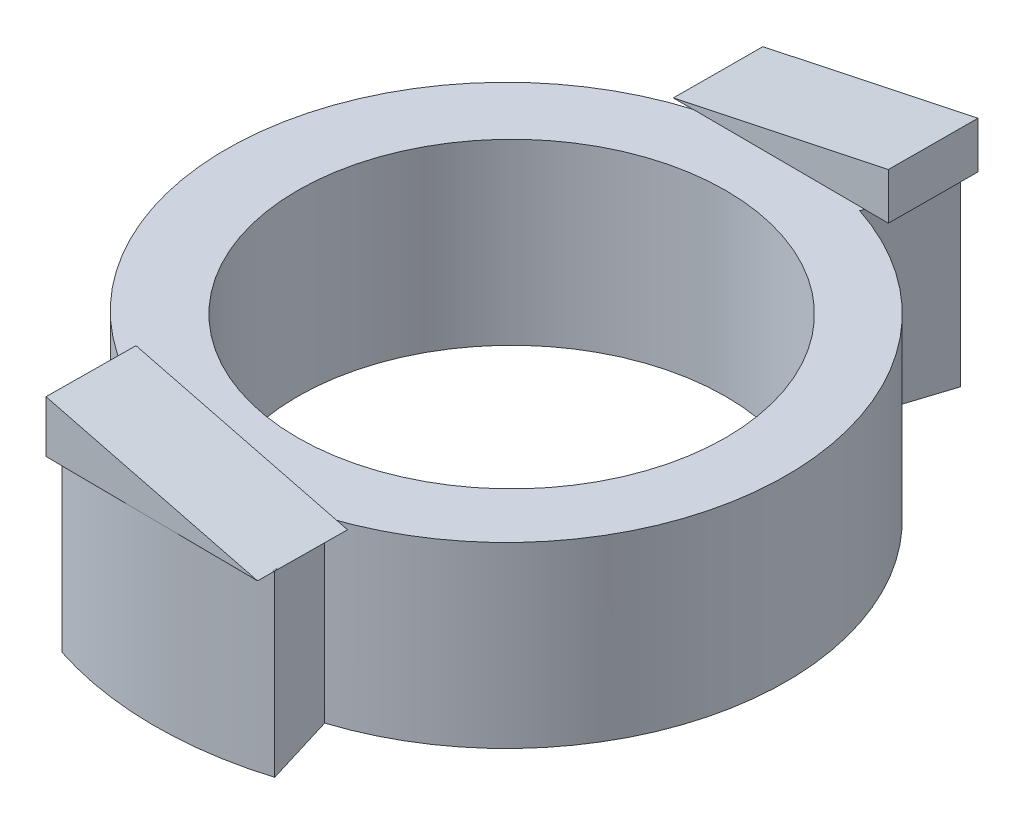
SolidWorks part; units mm, degrees
ref_plane "Front" through (0, 0, 0) normal (0, 0, 1) x (1, 0, 0)
ref_plane "Top" through (0, 0, 0) normal (0, 1, 0) x (1, 0, 0)
ref_plane "Right" through (0, 0, 0) normal (1, 0, 0) x (0, 0, -1)
sketch "Sketch1" plane through (0, 0, 0) normal (0, 1, 0) x (1, 0, 0)
  line L1 (0, -27.579) -> (0, 33.4967) construction
  line L2 (28.4514, 0) -> (-24.7523, 0) construction
  line L8 (-5.9389, 19.0979) -> (-4.6572, 15.0771)
  line L9 (6.1085, 19.0443) -> (4.7363, 14.7661)
  line L10 (-6.1958, -19.0161) -> (-4.8885, -15.0037)
  line L11 (5.8469, -19.1263) -> (4.6132, -15.0906)
  arc A5 (-6.1958, -19.0161) -> (5.8469, -19.1263) centre (0, 0) ccw
  arc A6 (6.1085, 19.0443) -> (-5.9389, 19.0979) centre (0, 0) ccw
  circle A9 centre (0, 0) radius 12
  arc A10 (-4.6572, 15.0771) -> (-4.8885, -15.0037) centre (-0.3123, 0.0024) ccw
  arc A11 (4.7363, 14.7661) -> (4.6132, -15.0906) centre (-0.1539, -0.1423) cw
  dimension "D1" = 15.69
extrude "Boss-Extrude1" add sketch "Sketch1" along normal blind 10
ref_plane "Plane1" through (-0.1829, 10, 19.9992) normal (-0.0091, 0, 1) x (1, 0, 0.0091)
sketch "Sketch2" plane through (-0.1829, 10, 19.9992) normal (-0.0091, 0, 1) x (1, 0, 0.0091)
  line L0 (-5.9712, -0.015) -> (5.9933, -0.015)
  line L1 (5.9933, -0.015) -> (-5.9712, 2.8853)
  line L2 (-5.9712, 2.8853) -> (-5.9712, -0.015)
extrude "Boss-Extrude2" add sketch "Sketch2" against normal blind 5
ref_plane "Plane2" through (0.0889, 10, -19.9998) normal (0.0044, 0, -1) x (-1, 0, -0.0044)
sketch "Sketch3" plane through (0.0889, 10, -19.9998) normal (0.0044, 0, -1) x (-1, 0, -0.0044)
  line L0 (-6.074, -0.0075) -> (6.036, -0.0075)
  line L1 (6.036, -0.0075) -> (-6.074, 2.6002)
  line L2 (-6.074, 2.6002) -> (-6.074, -0.0075)
extrude "Boss-Extrude3" add sketch "Sketch3" against normal blind 5
